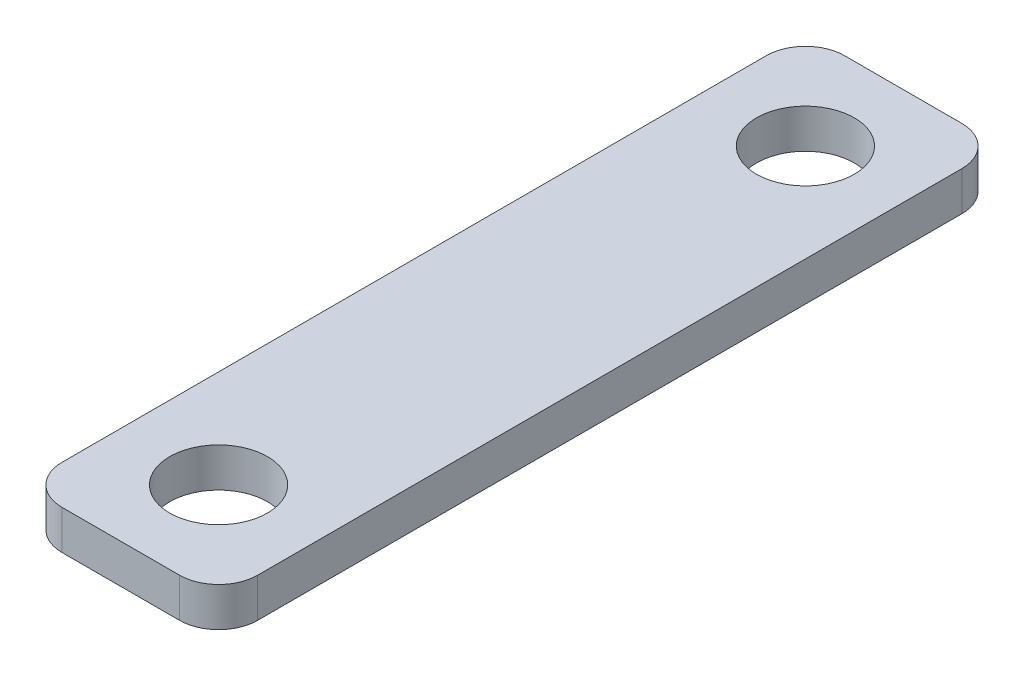
SolidWorks part; units mm, degrees
ref_plane "Front Plane" through (0, 0, 0) normal (0, 0, 1) x (1, 0, 0)
ref_plane "Top Plane" through (0, 0, 0) normal (0, 1, 0) x (1, 0, 0)
ref_plane "Right Plane" through (0, 0, 0) normal (1, 0, 0) x (0, 0, -1)
sketch "Sketch1" plane through (0, 0, 0) normal (0, 1, 0) x (1, 0, 0)
  line L1 (10, 0) -> (40, 0)
  line L2 (0, 10) -> (0, 190)
  line L3 (10, 200) -> (40, 200)
  line L4 (50, 10) -> (50, 190)
  arc A0 (40, 0) -> (50, 10) centre (40, 10) ccw
  arc A1 (10, 0) -> (0, 10) centre (10, 10) cw
  arc A2 (0, 190) -> (10, 200) centre (10, 190) cw
  arc A3 (40, 200) -> (50, 190) centre (40, 190) cw
  circle A4 centre (25, 25) radius 12.5
  circle A5 centre (25, 175) radius 12.5
  point P7 (50, 0)
  point P10 (0, 0)
  point P13 (0, 200)
  point P16 (50, 200)
  dimension "D3" = 10
  dimension "D4" = 25
  dimension "D1" = 200
  dimension "D2" = 50
  dimension "D5" = 25
  dimension "D6" = 25
  dimension "D7" = 25
extrude "Boss-Extrude1" add sketch "Sketch1" along normal blind 10
equation "\"D6@Sketch1\"=\"D5@Sketch1\""
